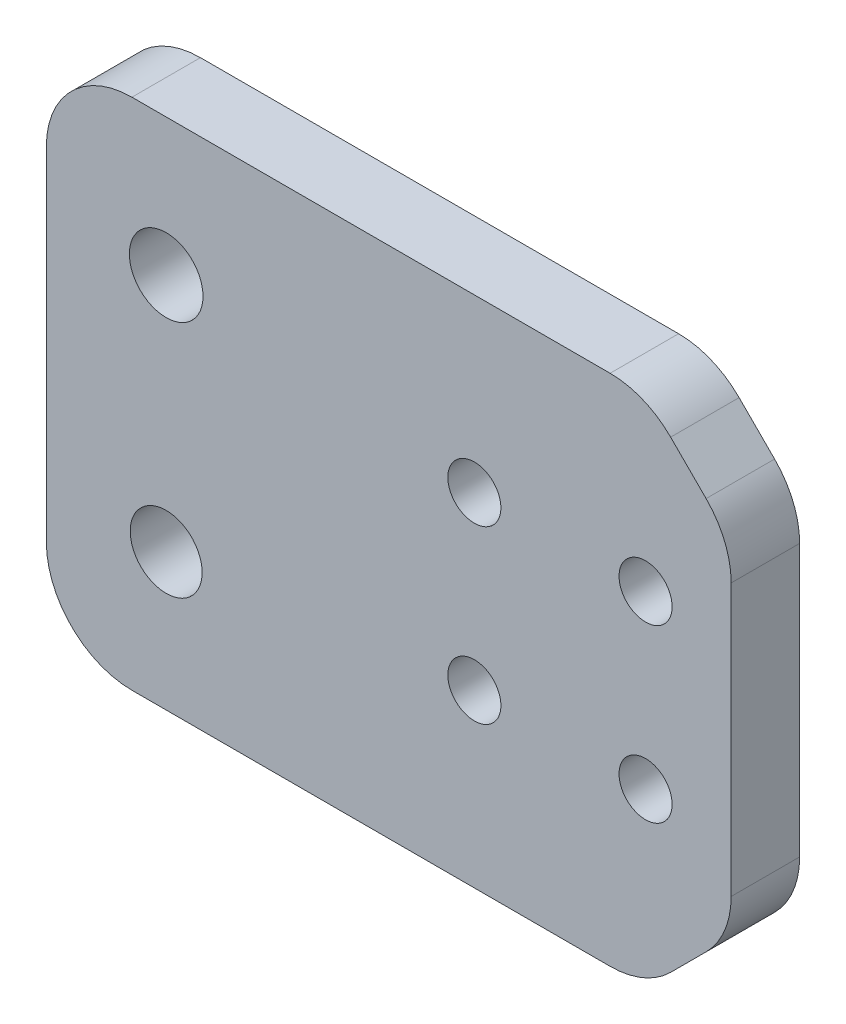
SolidWorks part; units mm, degrees
material "Thornel Mat VMA"
ref_plane "前视基准面" through (0, 0, 0) normal (0, 0, 1) x (1, 0, 0)
ref_plane "上视基准面" through (0, 0, 0) normal (0, 1, 0) x (1, 0, 0)
ref_plane "右视基准面" through (0, 0, 0) normal (1, 0, 0) x (0, 0, -1)
other "Configuration Table"
sketch "草图1" plane through (0, 0, 0) normal (0, 0, 1) x (1, 0, 0)
  line L0 (0, 15) -> (40, 15) construction
  line L1 (0, 0) -> (40, 0)
  line L2 (0, 0) -> (0, 30)
  line L3 (0, 30) -> (40, 30)
  line L4 (40, 0) -> (40, 30)
  circle A0 centre (7, 22) radius 2.15
  circle A1 centre (7, 8) radius 2.1
  circle A2 centre (35, 20) radius 1.55
  circle A3 centre (25, 20) radius 1.55
  circle A4 centre (25, 10) radius 1.55
  circle A5 centre (35, 10) radius 1.55
  point P9 (0, 15)
  dimension "D5" = 4.3
  dimension "D6" = 4.2
  dimension "D9" = 3.1
  dimension "D1" = 30
  dimension "D2" = 40
  dimension "D3" = 7
  dimension "D4" = 7
  dimension "D7" = 7
  dimension "D8" = 7
  dimension "D10" = 5
  dimension "D11" = 5
  dimension "D12" = 2
  dimension "D13" = 2
extrude "凸台-拉伸1" add sketch "草图1" along normal blind 4
chamfer "倒角1" distance 5 angle 45 2 edges at (40, 0, 2) (40, 30, 2)
fillet "圆角1" radius 5 6 edges at (35, 0, 2) (40, 5, 2) (40, 25, 2) (35, 30, 2) (0, 0, 2) (0, 30, 2)
